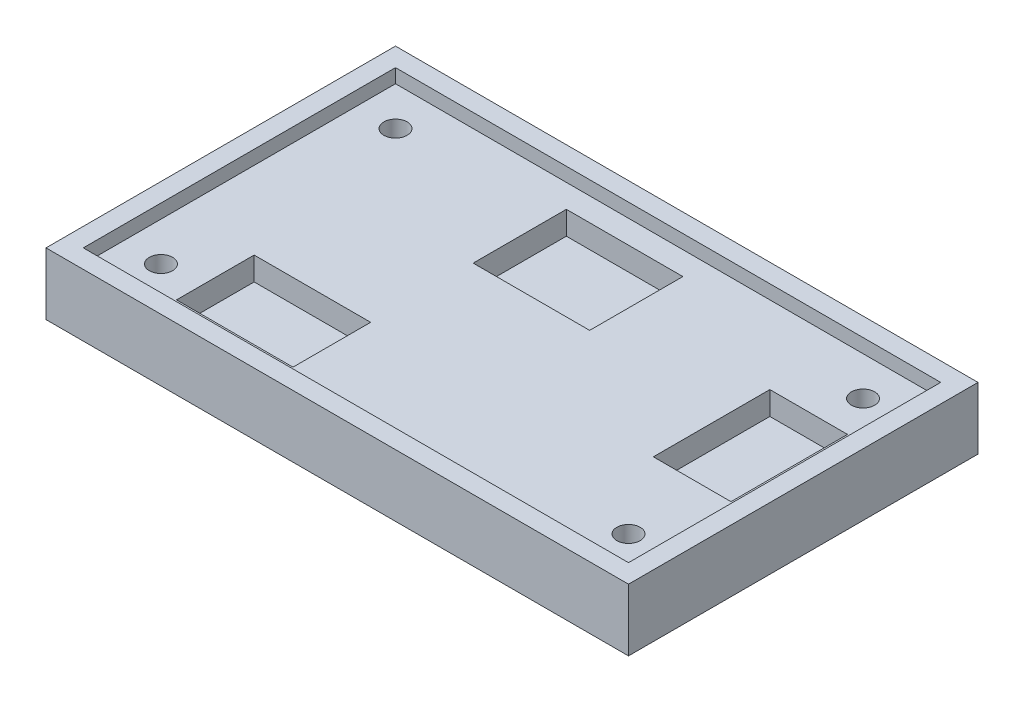
SolidWorks part; units mm, degrees
ref_plane "前视基准面" through (0, 0, 0) normal (0, 0, 1) x (1, 0, 0)
ref_plane "上视基准面" through (0, 0, 0) normal (0, 1, 0) x (1, 0, 0)
ref_plane "右视基准面" through (0, 0, 0) normal (1, 0, 0) x (0, 0, -1)
other "Configuration Table"
sketch "草图2" plane through (0, 0, 0) normal (0, 1, 0) x (1, 0, 0)
  line L1 (0, 0) -> (75, 0)
  line L2 (0, 0) -> (0, 45)
  line L3 (0, 45) -> (75, 45)
  line L4 (75, 0) -> (75, 45)
  dimension "D2" = 45
  dimension "D3" = 75
extrude "凸台-拉伸3" add sketch "草图2" along normal blind 8 contours L2 L1 L4 L3
sketch "草图5" plane through (0, 8, 0) normal (0, 1, 0) x (1, 0, 0)
  line L9 (2.4, 2.4) -> (72.6, 2.4)
  line L10 (72.6, 2.4) -> (72.6, 42.6)
  line L11 (72.6, 42.6) -> (2.4, 42.6)
  line L12 (2.4, 42.6) -> (2.4, 2.4)
  line L13 (2.4, 2.4) -> (72.6, 2.4)
  line L14 (72.6, 2.4) -> (72.6, 42.6)
  line L15 (72.6, 42.6) -> (2.4, 42.6)
  line L16 (2.4, 42.6) -> (2.4, 2.4)
  dimension "D1" = 2.4
extrude "切除-拉伸1" cut sketch "草图5" against normal blind 1.8 contours L13 L14 L15 L16
sketch "草图7" plane through (0, 6.2, 0) normal (0, 1, 0) x (1, 0, 0)
  line L0 (2.4, 42.6) -> (2.4, 2.4) construction
  line L1 (72.6, 42.6) -> (2.4, 42.6) construction
  line L6 (37.5, 42.5) -> (37.5, 50.7498) construction
  line L8 (2.5, 22.5) -> (6.7449, 22.5) construction
  circle A0 centre (7.4, 37.6) radius 1.5
  circle A1 centre (67.6, 37.6) radius 1.5
  circle A2 centre (7.4, 7.4) radius 1.5
  circle A3 centre (67.6, 7.4) radius 1.5
  dimension "D1" = 3
  dimension "D2" = 5
  dimension "D3" = 5
extrude "切除-拉伸4" cut sketch "草图7" against normal blind 2.2
sketch "草图8" plane through (0, 6.2, 0) normal (0, 1, 0) x (1, 0, 0)
  line L0 (2.4, 42.6) -> (2.4, 2.4) construction
  line L1 (12.4, 14.4) -> (27.4, 14.4)
  line L2 (12.4, 14.4) -> (12.4, 4.4)
  line L3 (12.4, 4.4) -> (27.4, 4.4)
  line L4 (27.4, 14.4) -> (27.4, 4.4)
  line L5 (2.4, 2.4) -> (72.6, 2.4) construction
  line L6 (2.4, 2.4) -> (72.6, 2.4) construction
  line L7 (72.6, 42.6) -> (2.4, 42.6) construction
  line L8 (60.6, 32.6) -> (70.6, 32.6)
  line L9 (60.6, 32.6) -> (60.6, 17.6)
  line L10 (60.6, 17.6) -> (70.6, 17.6)
  line L11 (70.6, 32.6) -> (70.6, 17.6)
  line L12 (72.6, 2.4) -> (72.6, 42.6) construction
  line L13 (72.6, 2.4) -> (72.6, 42.6) construction
  line L14 (72.6, 42.6) -> (2.4, 42.6) construction
  line L15 (27.4, 39.6) -> (42.4, 39.6)
  line L16 (27.4, 39.6) -> (27.4, 27.6)
  line L17 (27.4, 27.6) -> (42.4, 27.6)
  line L18 (42.4, 39.6) -> (42.4, 27.6)
  line L19 (2.4, 42.6) -> (2.4, 2.4) construction
  dimension "D1" = 10
  dimension "D2" = 15
  dimension "D3" = 2
  dimension "D4" = 12
  dimension "D5" = 25
  dimension "D6" = 12
  dimension "D7" = 2
  dimension "D8" = 10
  dimension "D9" = 25
  dimension "D10" = 15
  dimension "D11" = 3
  dimension "D12" = 40
extrude "切除-拉伸6" cut sketch "草图8" against normal blind 3
